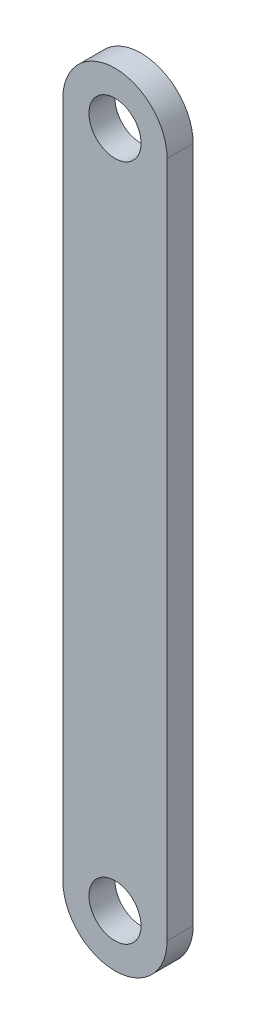
SolidWorks part; units mm, degrees
material "5052-H32"
ref_plane "Front Plane" through (0, 0, 0) normal (0, 0, 1) x (1, 0, 0)
ref_plane "Top Plane" through (0, 0, 0) normal (0, 1, 0) x (1, 0, 0)
ref_plane "Right Plane" through (0, 0, 0) normal (1, 0, 0) x (0, 0, -1)
sketch "Sketch1" plane through (0, 0, 0) normal (0, 0, 1) x (1, 0, 0)
  line L0 (-25.4, -330.2) -> (-25.4, 0)
  line L1 (25.4, 0) -> (25.4, -330.2)
  arc A0 (25.4, 0) -> (-25.4, 0) centre (0, 0) ccw
  arc A1 (-25.4, -330.2) -> (25.4, -330.2) centre (0, -330.2) ccw
  circle A2 centre (0, 0) radius 12.7
  circle A3 centre (0, -330.2) radius 12.7
  dimension "D1" = 25.4
  dimension "D3" = 25.4
  dimension "D4" = 25.4
  dimension "D2" = 330.2
extrude "Boss-Extrude1" add sketch "Sketch1" along normal blind 12.7
